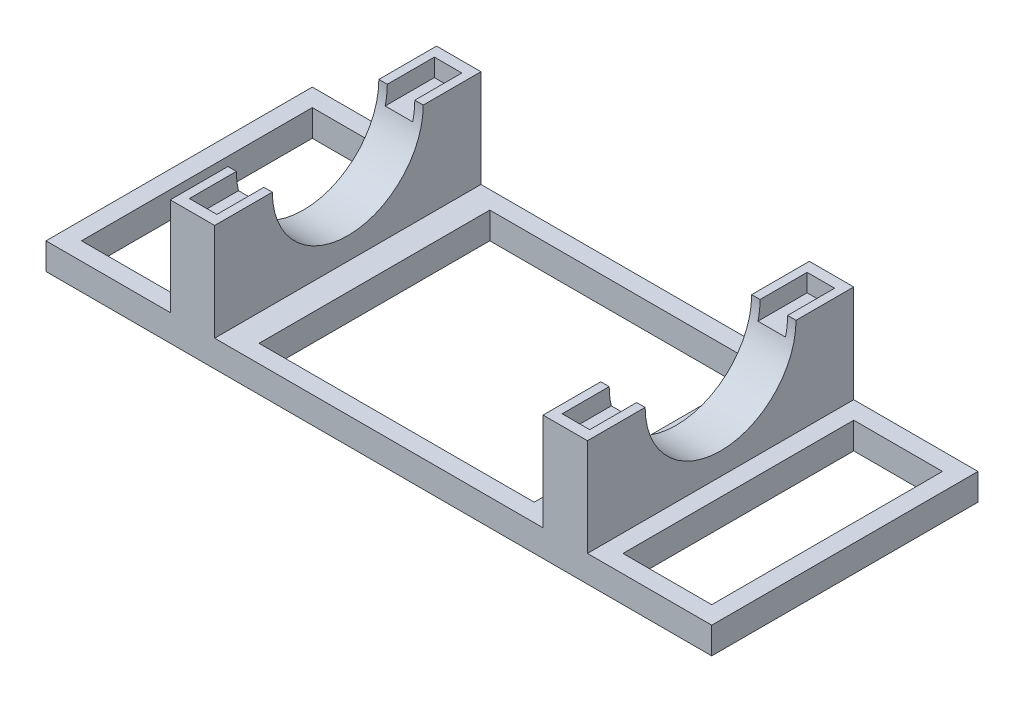
SolidWorks part; units mm, degrees
ref_plane "前视基准面" through (0, 0, 0) normal (0, 0, 1) x (1, 0, 0)
ref_plane "上视基准面" through (0, 0, 0) normal (0, 1, 0) x (1, 0, 0)
ref_plane "右视基准面" through (0, 0, 0) normal (1, 0, 0) x (0, 0, -1)
sketch "草图1" plane through (0, 0, 0) normal (0, 1, 0) x (1, 0, 0)
  line L1 (-75, 30) -> (75, 30)
  line L2 (-75, 30) -> (-75, -30)
  line L3 (-75, -30) -> (75, -30)
  line L4 (75, 30) -> (75, -30)
  line L5 (-75, 30) -> (75, -30) construction
  line L6 (-75, -30) -> (75, 30) construction
  point P0 (0, 0)
  dimension "D1" = 150
  dimension "D2" = 60
extrude "凸台-拉伸1" add sketch "草图1" along normal blind 6
sketch "草图2" plane through (0, 6, 0) normal (0, 1, 0) x (1, 0, 0)
  line L0 (75, 30) -> (-75, 30) construction
  line L1 (-47, 30) -> (-37, 30)
  line L2 (-47, 30) -> (-47, -30)
  line L3 (-47, -30) -> (-37, -30)
  line L4 (-37, 30) -> (-37, -30)
  line L5 (-75, -30) -> (75, -30) construction
  line L6 (0, 43.9515) -> (0, -51.5741) construction
  line L7 (47, -30) -> (37, -30)
  line L8 (37, 30) -> (37, -30)
  line L9 (47, 30) -> (37, 30)
  line L10 (47, 30) -> (47, -30)
  dimension "D1" = 10
  dimension "D2" = 47
extrude "凸台-拉伸2" add sketch "草图2" along normal blind 22
sketch "草图3" plane through (0, 28, 0) normal (0, 1, 0) x (1, 0, 0)
  line L6 (-42, 30) -> (-42, 27.6) construction
  line L7 (-45.1, 27.6) -> (-38.9, 27.6)
  line L8 (-45.1, 27.6) -> (-45.1, -27.6)
  line L9 (-45.1, -27.6) -> (-38.9, -27.6)
  line L10 (-38.9, 27.6) -> (-38.9, -27.6)
  line L11 (-37, 30) -> (-47, 30) construction
  line L12 (-47, 0) -> (-45.1, 0) construction
  line L13 (-47, 30) -> (-47, -30) construction
  line L14 (0, 42.3275) -> (0, -45.4976) construction
  line L15 (45.1, -27.6) -> (38.9, -27.6)
  line L16 (38.9, 27.6) -> (38.9, -27.6)
  line L17 (45.1, 27.6) -> (38.9, 27.6)
  line L18 (45.1, 27.6) -> (45.1, -27.6)
  dimension "D1" = 6.2
  dimension "D2" = 55.2
extrude "切除-拉伸1" cut sketch "草图3" against normal blind 4
sketch "草图4" plane through (-47, 0, 0) normal (-1, 0, 0) x (0, 0, 1)
  line L0 (-30, 28) -> (30, 28) construction
  circle A0 centre (0, 28) radius 17
  dimension "D1" = 34
extrude "切除-拉伸2" cut sketch "草图4" against normal through all
sketch "草图5" plane through (0, 6, 0) normal (0, 1, 0) x (1, 0, 0)
  line L0 (-47, 30) -> (-75, 30) construction
  line L1 (-71, 26) -> (-51, 26)
  line L2 (-71, 26) -> (-71, -26)
  line L3 (-71, -26) -> (-51, -26)
  line L4 (-51, 26) -> (-51, -26)
  line L5 (-75, 30) -> (-75, -30) construction
  line L7 (-47, -17) -> (-47, -30) construction
  line L8 (-75, -30) -> (-47, -30) construction
  line L9 (0, 50.0232) -> (0, -53.6723) construction
  line L10 (71, -26) -> (51, -26)
  line L11 (51, 26) -> (51, -26)
  line L12 (71, 26) -> (51, 26)
  line L13 (71, 26) -> (71, -26)
  line L14 (37, 30) -> (-37, 30) construction
  line L15 (-31, 26) -> (31, 26)
  line L16 (-31, 26) -> (-31, -26)
  line L17 (-31, -26) -> (31, -26)
  line L18 (31, 26) -> (31, -26)
  line L20 (-37, -30) -> (-37, 30) construction
  line L21 (37, 17) -> (37, -17) construction
  line L22 (-37, -30) -> (37, -30) construction
  dimension "D1" = 4
  dimension "D2" = 4
  dimension "D3" = 4
  dimension "D4" = 4
  dimension "D5" = 4
  dimension "D6" = 6
  dimension "D7" = 6
  dimension "D8" = 4
extrude "切除-拉伸3" cut sketch "草图5" against normal through all
